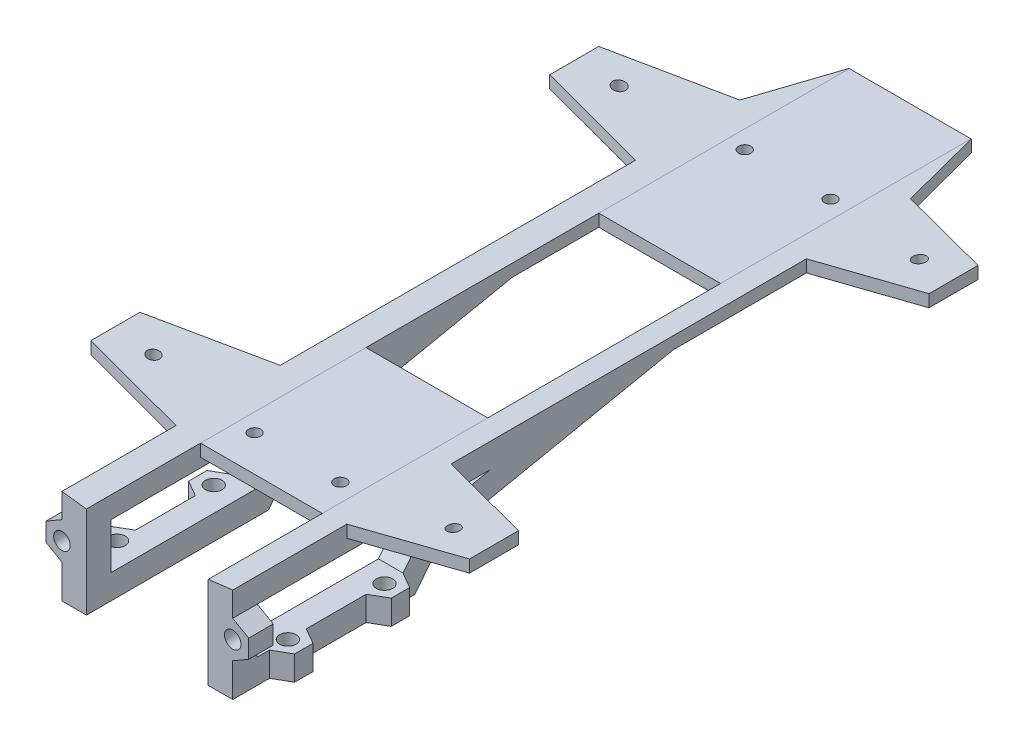
SolidWorks part; units mm, degrees
ref_plane "前视基准面" through (0, 0, 0) normal (0, 0, 1) x (1, 0, 0)
ref_plane "上视基准面" through (0, 0, 0) normal (0, 1, 0) x (1, 0, 0)
ref_plane "右视基准面" through (0, 0, 0) normal (1, 0, 0) x (0, 0, -1)
sketch "草图1" plane through (0, 0, 0) normal (0, 1, 0) x (1, 0, 0)
  line L1 (-1, 1) -> (1, 1)
  line L2 (-1, 1) -> (-1, -1)
  line L3 (-1, -1) -> (1, -1)
  line L4 (1, 1) -> (1, -1)
  line L5 (-1, 1) -> (1, -1) construction
  line L6 (-1, -1) -> (1, 1) construction
  point P0 (0, 0)
  dimension "D1" = 2
  dimension "D2" = 2
extrude "凸台-拉伸1" add sketch "草图1" along normal blind 3
sketch "草图2" plane through (0, 0, -1) normal (0, 0, -1) x (-1, 0, 0)
  line L0 (-9.4392, 3) -> (10.4392, 3)
  line L1 (10.4392, 3) -> (31.448, 5.562)
  line L2 (-9.4392, 3) -> (-30.448, 5.562)
  line L3 (-30.448, 5.562) -> (-30.448, 3.562)
  line L4 (31.448, 5.562) -> (31.448, 3.562)
  line L7 (10.4392, 1) -> (31.448, 3.562)
  line L8 (10.4392, 1) -> (-9.4392, 1)
  line L9 (-30.448, 3.562) -> (-9.4392, 1)
  dimension "D1" = 2
  dimension "D2" = 2
  dimension "D3" = 2
  dimension "D4" = 2
extrude "凸台-拉伸2" add sketch "草图2" against normal up to vertex (124.5 mm away)
sketch "草图3" plane through (0, 1, 0) normal (0, -1, 0) x (1, 0, 0)
  line L1 (2.6356, -2.1863) -> (-3.4682, -2.1863)
  line L2 (2.6356, -2.1863) -> (2.6356, 5.0301)
  line L3 (2.6356, 5.0301) -> (-3.4682, 5.0301)
  line L4 (-3.4682, -2.1863) -> (-3.4682, 5.0301)
extrude "切除-拉伸1" cut sketch "草图3" along normal blind 100
sketch "草图4" plane through (0, 1, 0) normal (0, -1, 0) x (1, 0, 0)
  circle A0 centre (24, 98) radius 1
  circle A1 centre (6.5002, 99) radius 1
  circle A2 centre (-7.4998, 99) radius 1
  circle A3 centre (-24.9999, 98) radius 1
  circle A4 centre (6.5002, 19) radius 1
  circle A5 centre (-7.4998, 19) radius 1
  circle A6 centre (24, 22) radius 1.05
  circle A7 centre (-24.9999, 22) radius 1.05
extrude "切除-拉伸2" cut sketch "草图4" against normal blind 100
sketch "草图6" plane through (0, 1, 0) normal (0, -1, 0) x (1, 0, 0)
  line L0 (-31.448, 18.8759) -> (-14.4392, 12.8759)
  line L1 (-31.448, 123.5) -> (-31.448, -1) construction
  line L2 (-14.4392, 12.8759) -> (-10.4392, -1.1241)
  line L3 (-10.4392, -3) -> (-10.4392, 0.7518) construction
  line L4 (-10.4392, -1.1241) -> (9.4392, -1.1241)
  line L5 (9.4392, 0.7518) -> (9.4392, -3) construction
  line L6 (9.4392, -1.1241) -> (13.4392, 12.8759)
  line L7 (13.4392, 12.8759) -> (30.448, 18.8759)
  line L8 (30.448, 123.5) -> (30.448, -1) construction
  line L9 (30.448, 18.8759) -> (30.448, 26.8759)
  line L10 (30.448, 26.8759) -> (13.4392, 29.8759)
  line L11 (13.4392, 29.8759) -> (13.4392, 87.8759)
  line L12 (13.4392, 87.8759) -> (30.448, 93.8759)
  line L13 (30.448, 93.8759) -> (30.448, 101.8759)
  line L14 (30.448, 101.8759) -> (13.4392, 104.8759)
  line L15 (13.4392, 104.8759) -> (13.4392, 123.5)
  line L16 (13.4392, 123.5) -> (-14.4392, 123.5)
  line L17 (-14.4392, 123.5) -> (-14.4392, 104.8759)
  line L18 (-14.4392, 104.8759) -> (-31.3297, 101.8759)
  line L19 (-31.3297, 101.8759) -> (-31.3297, 93.8759)
  line L20 (-31.3297, 93.8759) -> (-14.4392, 87.8759)
  line L21 (-14.4392, 87.8759) -> (-14.4392, 29.8759)
  line L22 (-14.4392, 29.8759) -> (-31.448, 26.8759)
  line L23 (-31.448, 26.8759) -> (-31.448, 18.8759)
  line L24 (9.4392, 123.5) -> (9.4392, -1) construction
  line L25 (-10.4392, 123.5) -> (-10.4392, -1) construction
  line L26 (-10.4392, 123.5) -> (-31.448, 123.5) construction
  line L28 (37.8818, -17.2071) -> (-39.0522, -17.2071)
  line L29 (37.8818, -17.2071) -> (37.8818, 130.0379)
  line L30 (37.8818, 130.0379) -> (-39.0522, 130.0379)
  line L31 (-39.0522, -17.2071) -> (-39.0522, 130.0379)
  dimension "D1" = 8
  dimension "D2" = 8
  dimension "D3" = 14
  dimension "D4" = 14
  dimension "D5" = 20
  dimension "D6" = 20
  dimension "D7" = 31
  dimension "D8" = 31
  dimension "D9" = 4
  dimension "D10" = 4
  dimension "D11" = 4
  dimension "D12" = 58
  dimension "D13" = 58
  dimension "D14" = 8
  dimension "D15" = 8
  dimension "D16" = 95
  dimension "D17" = 95
  dimension "D18" = 4
  dimension "D19" = 4
  dimension "D20" = 17
  dimension "D21" = 0
extrude "切除-拉伸3" cut sketch "草图6" against normal blind 100
sketch "草图7" plane through (0, 0, 123.5) normal (0, 0, 1) x (1, 0, 0)
  line L0 (-14.4392, 1.4878) -> (-10.4392, 1)
  line L1 (-14.4392, 1.4878) -> (-14.4392, 1)
  line L3 (-10.4392, 1) -> (-10.4392, -12)
  line L4 (-10.4392, -12) -> (-14.4392, -12)
  line L5 (-14.4392, 1) -> (-14.4392, -12)
  dimension "D1" = 13
extrude "凸台-拉伸3" add sketch "草图7" against normal blind 2
sketch "草图8" plane through (-14.4392, 0, 0) normal (-1, 0, 0) x (0, 0, 1)
  line L0 (51.5878, 1.4878) -> (121.5, 1.4878)
  line L1 (121.5, 1.4878) -> (104.8759, 1.4878) construction
  line L2 (121.5, 1.4878) -> (121.5, -12)
  line L3 (121.5, -12) -> (93.8043, -12)
  line L4 (51.5878, 1.4878) -> (89.1247, -6.1693)
  line L5 (89.1247, -6.1693) -> (93.8043, -12)
  line L6 (87.8759, 1.4878) -> (29.8759, 1.4878) construction
  line L7 (81.4049, -0.5122) -> (119.5, -0.5122)
  line L8 (119.5, -0.5122) -> (119.5, -8)
  line L9 (119.5, -8) -> (106.7376, -8)
  line L12 (92.7049, -4.2396) -> (95.723, -8)
  line L13 (95.723, -8) -> (106.7376, -8)
  line L14 (92.7049, -4.2396) -> (91.3399, -2.5388)
  line L15 (91.3399, -2.5388) -> (81.4049, -0.5122)
  point P16 (86.275, -0.5122)
  point P18 (95.9471, -12)
  point P19 (51.6031, 1.4878)
  point P20 (94.132, -12)
  point P21 (89.5166, -6.2493)
  point P22 (89.5166, -6.2493)
  dimension "D1" = 4
  dimension "D2" = 180
  dimension "D3" = 2
  dimension "D4" = 2
  dimension "D5" = 4
  dimension "D6" = 4
extrude "凸台-拉伸4" add sketch "草图8" against normal blind 4
sketch "草图9" plane through (0, 3, 0) normal (0, 1, 0) x (1, 0, 0)
  line L0 (-10.4392, -123.5) -> (-10.4392, 1) construction
  line L1 (-10.4392, -104.8759) -> (9.4392, -104.8759)
  line L2 (-10.4392, -104.8759) -> (-10.4392, -123.5)
  line L3 (-10.4392, -123.5) -> (9.4392, -123.5)
  line L4 (9.4392, -104.8759) -> (9.4392, -123.5)
  dimension "D1" = 0
extrude "切除-拉伸4" cut sketch "草图9" against normal blind 4
sketch "草图10" plane through (0, 3, 0) normal (0, 1, 0) x (1, 0, 0)
  line L0 (-10.4392, -104.8759) -> (-10.4392, 1) construction
  line L1 (-10.4392, -39.8759) -> (9.4392, -39.8759)
  line L2 (-10.4392, -39.8759) -> (-10.4392, -77.8759)
  line L3 (-10.4392, -77.8759) -> (9.4392, -77.8759)
  line L4 (9.4392, -39.8759) -> (9.4392, -77.8759)
  line L5 (9.4392, -104.8759) -> (9.4392, 1) construction
  dimension "D1" = 10
  dimension "D2" = 10
extrude "切除-拉伸5" cut sketch "草图10" against normal blind 4
sketch "草图11" plane through (0, -12, 0) normal (0, -1, 0) x (1, 0, 0)
  line L0 (-14.4392, 93.8043) -> (-14.4392, 123.5) construction
  line L1 (-14.4392, 95.723) -> (-14.4392, 101.723)
  line L3 (-14.4392, 123.5) -> (-10.4392, 123.5) construction
  line L4 (-14.4392, 101.723) -> (-17.0373, 100.223)
  line L5 (-17.0373, 100.223) -> (-17.0373, 97.223)
  line L6 (-17.0373, 97.223) -> (-14.4392, 95.723)
  line L7 (-14.4392, 95.723) -> (-11.8412, 97.223)
  line L8 (-11.8412, 97.223) -> (-11.8412, 100.223)
  line L9 (-11.8412, 100.223) -> (-14.4392, 101.723)
  line L16 (-14.4392, 117.5) -> (-17.0373, 116)
  line L17 (-17.0373, 116) -> (-17.0373, 113)
  line L18 (-17.0373, 113) -> (-14.4392, 111.5)
  line L19 (-14.4392, 111.5) -> (-11.8412, 113)
  line L20 (-11.8412, 113) -> (-11.8412, 116)
  line L21 (-11.8412, 116) -> (-14.4392, 117.5)
  circle A2 centre (-14.4392, 98.723) radius 2.5981 construction
  circle A4 centre (-14.4392, 114.5) radius 2.5981 construction
  dimension "D2" = 6
  dimension "D4" = 0
extrude "凸台-拉伸6" add sketch "草图11" against normal blind 4
sketch "草图13" plane through (0, 0, 123.5) normal (0, 0, 1) x (1, 0, 0)
  line L0 (-14.4392, -12) -> (-14.4392, 3.4878) construction
  line L2 (-14.4392, -0.5122) -> (-17.0373, -2.0122)
  line L3 (-17.0373, -2.0122) -> (-17.0373, -5.0122)
  line L4 (-17.0373, -5.0122) -> (-14.4392, -6.5122)
  line L5 (-14.4392, -6.5122) -> (-11.8412, -5.0122)
  line L6 (-11.8412, -5.0122) -> (-11.8412, -2.0122)
  line L7 (-11.8412, -2.0122) -> (-14.4392, -0.5122)
  circle A0 centre (-14.4392, -3.5122) radius 3
  circle A1 centre (-14.4392, -3.5122) radius 2.5981 construction
  line M3 (-14.4392, 3.4878) -> (-14.4392, -12)
  dimension "D1" = 6
  dimension "D2" = 4
extrude "凸台-拉伸7" add sketch "草图13" against normal blind 4 contours L3 L4 L2 M3
sketch "草图14" plane through (0, 0, 123.5) normal (0, 0, 1) x (1, 0, 0)
  circle A0 centre (-14.4392, -3.5122) radius 1.35
  dimension "D2" = 2.7
  dimension "D1" = 3
extrude "切除-拉伸7" cut sketch "草图14" against normal blind 4
sketch "草图15" plane through (0, -12, 0) normal (0, -1, 0) x (1, 0, 0)
  circle A0 centre (-14.4392, 98.723) radius 1.35
  circle A1 centre (-14.4392, 114.5) radius 1.35
  dimension "D1" = 2.7
  dimension "D2" = 2.7
  dimension "D3" = 3
  dimension "D4" = 3
extrude "切除-拉伸8" cut sketch "草图15" against normal blind 4
ref_plane "基准面1" through (-0.5, 0, 0) normal (-1, 0, 0) x (0, 0, 1)
mirror "镜向1" about plane through (-0.5, 0, 0) normal (-1, 0, 0) of "切除-拉伸8", "切除-拉伸7", "凸台-拉伸7", "凸台-拉伸6", "切除-拉伸5", "切除-拉伸4", "凸台-拉伸4", "凸台-拉伸3"
